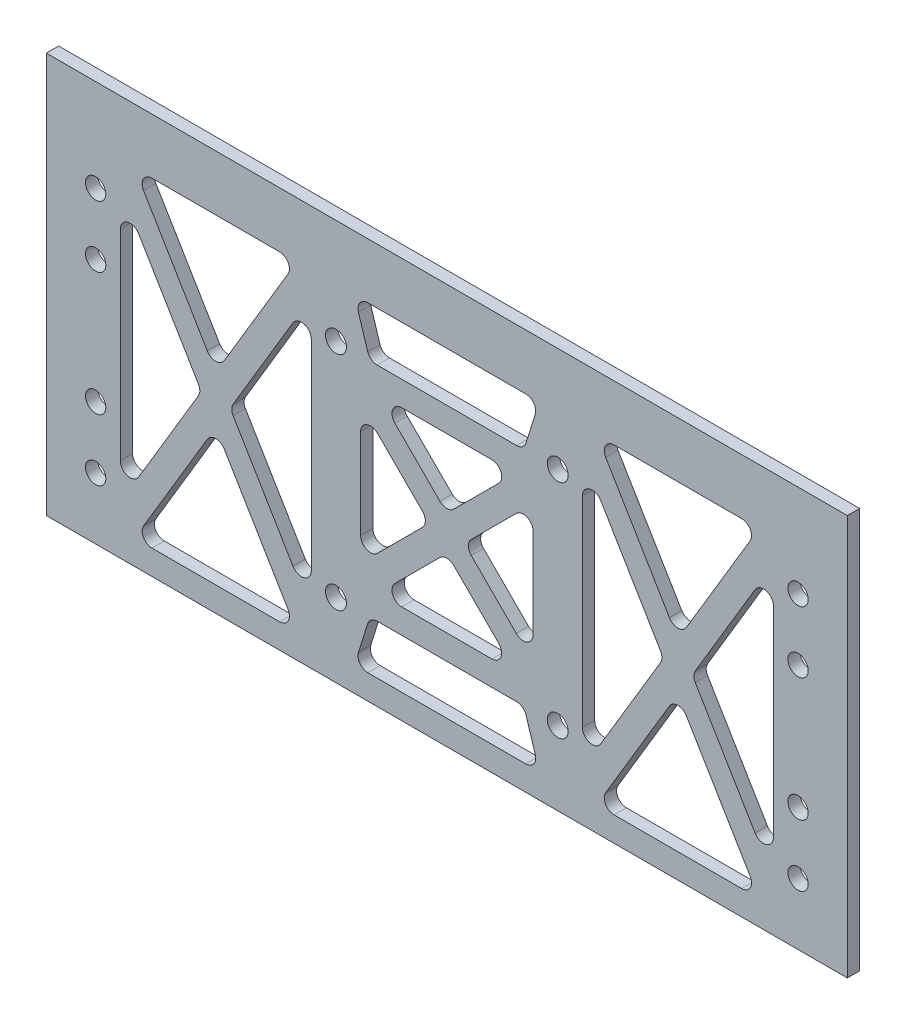
SolidWorks part; units mm, degrees
material "黑板"
ref_plane "前视基准面" through (0, 0, 0) normal (0, 0, 1) x (1, 0, 0)
ref_plane "上视基准面" through (0, 0, 0) normal (0, 1, 0) x (1, 0, 0)
ref_plane "右视基准面" through (0, 0, 0) normal (1, 0, 0) x (0, 0, -1)
sketch "草图1" plane through (0, 0, 0) normal (0, 0, 1) x (1, 0, 0)
  line L1 (-65, 30) -> (65, 30)
  line L2 (-65, 30) -> (-65, -30)
  line L3 (-65, -30) -> (65, -30)
  line L4 (65, 30) -> (65, -30)
  line L5 (-65, 30) -> (65, -30) construction
  line L6 (-65, -30) -> (65, 30) construction
  point P0 (0, 0)
  dimension "D1" = 130
  dimension "D2" = 60
extrude "凸台-拉伸1" add sketch "草图1" along normal blind 2
sketch "草图2" plane through (0, 0, 2) normal (0, 0, 1) x (1, 0, 0)
  line L0 (-57, -20) -> (-57, -10) construction
  line L1 (-65, 30) -> (-65, -30) construction
  line L2 (-65, -30) -> (65, -30) construction
  line L3 (0, 0) -> (0, -47.9971) construction
  line L4 (0, 0) -> (24.9529, 0) construction
  circle A1 centre (-57, -10) radius 1.65
  circle A3 centre (-57, -20) radius 1.65
  circle A4 centre (57, -10) radius 1.65
  circle A5 centre (57, -20) radius 1.65
  circle A6 centre (57, 20) radius 1.65
  circle A7 centre (57, 10) radius 1.65
  circle A8 centre (-57, 20) radius 1.65
  circle A9 centre (-57, 10) radius 1.65
  dimension "D2" = 3.3
  dimension "D4" = 10
  dimension "D1" = 10
  dimension "D3" = 8
extrude "切除-拉伸1" cut sketch "草图2" against normal through all
sketch "草图3" plane through (0, 0, 2) normal (0, 0, 1) x (1, 0, 0)
  line L1 (-18, 18) -> (18, 18) construction
  line L2 (-18, 18) -> (-18, -18) construction
  line L3 (-18, -18) -> (18, -18) construction
  line L4 (18, 18) -> (18, -18) construction
  line L5 (-18, 18) -> (18, -18) construction
  line L6 (-18, -18) -> (18, 18) construction
  circle A0 centre (-18, 18) radius 1.7
  circle A1 centre (-18, -18) radius 1.7
  circle A2 centre (18, 18) radius 1.7
  circle A3 centre (18, -18) radius 1.7
  point P0 (0, 0)
  dimension "D2" = 3.4
  dimension "D1" = 36
extrude "切除-拉伸2" cut sketch "草图3" against normal through all
sketch "草图4" plane through (0, 0, 2) normal (0, 0, 1) x (1, 0, 0)
  line L0 (-18, 18) -> (-18, -18) construction
  line L1 (-18, -18) -> (18, -18) construction
  line L2 (18, -18) -> (18, 18) construction
  line L3 (18, 18) -> (-18, 18) construction
  line L4 (-57, 20) -> (-57, 10) construction
  line L5 (-53, 26) -> (-53, -26)
  line L6 (-53, -26) -> (-22, -26)
  line L7 (-22, -26) -> (-22, 26)
  line L8 (-22, 26) -> (-53, 26)
  line L9 (65, 30) -> (-65, 30) construction
  line L14 (-65, -30) -> (65, -30) construction
  line L15 (0, 0) -> (0, -36.6692) construction
  line L16 (22, -26) -> (22, 26)
  line L17 (53, -26) -> (22, -26)
  line L18 (53, 26) -> (53, -26)
  line L19 (22, 26) -> (53, 26)
  line L20 (14, 14) -> (-14, 14)
  line L21 (-14, 14) -> (-14, -14)
  line L22 (-14, -14) -> (14, -14)
  line L23 (14, -14) -> (14, 14)
  line L24 (-15, 26) -> (-12.5, 18)
  line L25 (-12.5, 18) -> (12.5, 18)
  line L26 (12.5, 18) -> (15, 26)
  line L27 (15, 26) -> (-15, 26)
  line L28 (0, 0) -> (40.7826, 0) construction
  line L29 (12.5, -18) -> (15, -26)
  line L30 (-12.5, -18) -> (12.5, -18)
  line L31 (-15, -26) -> (-12.5, -18)
  line L32 (15, -26) -> (-15, -26)
  dimension "D1" = 4
  dimension "D2" = 4
  dimension "D3" = 4
  dimension "D4" = 4
  dimension "D5" = 4
  dimension "D6" = 30
  dimension "D7" = 25
extrude "切除-拉伸4" cut sketch "草图4" against normal through all
sketch "草图5" plane through (0, 0, 2) normal (0, 0, 1) x (1, 0, 0)
  line L0 (-53, 26) -> (-22, -26)
  line L1 (-22, 26) -> (-53, -26)
  line L2 (-53, 26) -> (-53, -26) construction
  line L3 (-53, -26) -> (-22, -26) construction
  line L4 (22, 26) -> (53, -26)
  line L5 (22, -26) -> (53, 26)
  line L6 (-14, 14) -> (14, -14)
  line L7 (-14, -14) -> (14, 14)
  line L8 (14, -14) -> (14, 14) construction
  line L9 (14, 14) -> (-14, 14) construction
  point P28 (14, 13.1137)
  point P29 (0, 0)
  point P30 (0, 0)
extrude "拉伸-薄壁1" add sketch "草图5" against normal through all thin thin type mid plane wall 4
fillet "圆角1" radius 1.6 44 edges at (-15, 26, 1) (-12.5, 18, 1) (12.5, 18, 1) (15, 26, 1) (-12.5, -18, 1) (-15, -26, 1) (15, -26, 1) (12.5, -18, 1) (-35.1716, 0, 1) (-22, -22.0942, 1) (-22, 22.0942, 1) (-37.5, -3.9058, 1) (-50.6716, -26, 1) (-24.3284, -26, 1) (-37.5, 3.9058, 1) (-24.3284, 26, 1) (-50.6716, 26, 1) (-53, -22.0942, 1) (-39.8284, 0, 1) (-53, 22.0942, 1) (37.5, 3.9058, 1) (50.6716, 26, 1) (24.3284, 26, 1) (39.8284, 0, 1) (53, -22.0942, 1) (35.1716, 0, 1) (22, 22.0942, 1) (22, -22.0942, 1) (50.6716, -26, 1) (37.5, -3.9058, 1) (24.3284, -26, 1) (14, 11.1716, 1) (2.8284, 0, 1) (14, -11.1716, 1) (0, -2.8284, 1) (-11.1716, -14, 1) (11.1716, -14, 1) (0, 2.8284, 1) (11.1716, 14, 1) (-11.1716, 14, 1) (-14, -11.1716, 1) (-2.8284, 0, 1) (-14, 11.1716, 1) (53, 22.0942, 1)
sketch "草图6" plane through (0, 30, 0) normal (0, 1, 0) x (1, 0, 0)
  line L4 (65, 0) -> (-65, 0)
  line L5 (-65, 0) -> (-65, -2)
  line L6 (-65, -2) -> (65, -2)
  line L7 (65, -2) -> (65, 0)
  line L8 (65, 0) -> (-65, 0)
  line L9 (-65, 0) -> (-65, -2)
  line L10 (-65, -2) -> (65, -2)
  line L11 (65, -2) -> (65, 0)
  dimension "D1" = 0
extrude "凸台-拉伸2" add sketch "草图6" along normal blind 5
